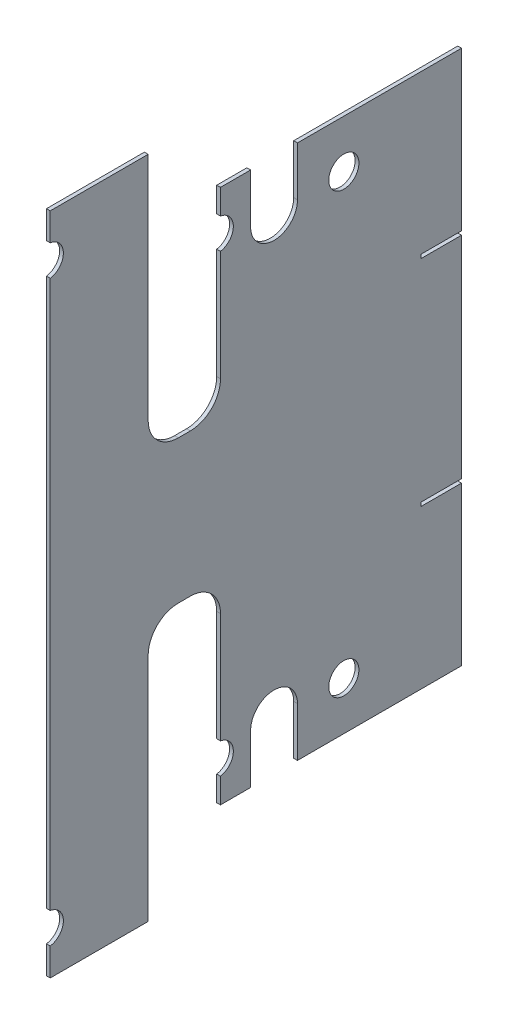
SolidWorks part; units mm, degrees
material "Custom Plastic"
ref_plane "X-Y Datum" through (0, 0, 0) normal (0, 0, 1) x (1, 0, 0)
ref_plane "X-Z Datum" through (0, 0, 0) normal (0, 1, 0) x (1, 0, 0)
ref_plane "Y-Z Datum" through (0, 0, 0) normal (1, 0, 0) x (0, 0, -1)
ref_plane "Plane1" through (-573.7606, 0, 0) normal (-1, 0, 0) x (0, 0, 1)
sketch "Sketch1" plane through (-573.7606, 0, 0) normal (-1, 0, 0) x (0, 0, 1)
  line L0 (55, 0) -> (-55, 0) construction
  line L1 (38.1, 225.425) -> (38.1, 183.8691)
  line L2 (-105.5624, -92.075) -> (-105.5624, -88.9)
  line L3 (-105.5624, 88.9) -> (-105.5624, 92.075)
  line L4 (-105.5624, 92.075) -> (-139.7, 92.075)
  line L5 (-105.5624, 88.9) -> (-139.7, 88.9)
  line L6 (-105.5624, -88.9) -> (-139.7, -88.9)
  line L7 (-139.7, -88.9) -> (-139.7, 88.9)
  line L8 (-139.7, 92.075) -> (-139.7, 225.425)
  line L9 (-139.7, 225.425) -> (-1.4023, 225.425)
  line L10 (-105.5624, -92.075) -> (-139.7, -92.075)
  line L11 (-139.7, -92.075) -> (-139.7, -225.425)
  line L12 (-139.7, -225.425) -> (-1.4023, -225.425)
  line L13 (63.5, -225.425) -> (63.5, -60.325)
  line L14 (63.5, 225.425) -> (63.5, 60.325)
  line L15 (63.5, -60.325) -> (124.46, -60.325)
  line L16 (63.5, 60.325) -> (124.46, 60.325)
  line L19 (207.01, 280.035) -> (124.46, 280.035)
  line L20 (124.46, 280.035) -> (124.46, 60.325)
  line L22 (207.01, -280.035) -> (124.46, -280.035)
  line L23 (124.46, -280.035) -> (124.46, -60.325)
  line L26 (207.01, -280.035) -> (207.01, 280.035)
  line L27 (-1.4023, 183.8691) -> (-1.4023, 225.425)
  line L28 (38.1, 225.425) -> (63.5, 225.425)
  line L29 (-1.4023, -183.8691) -> (-1.4023, -225.425)
  line L30 (38.1, -225.425) -> (38.1, -183.8691)
  line L31 (38.1, -225.425) -> (63.5, -225.425)
  arc A0 (38.1, 183.8691) -> (-1.4023, 183.8691) centre (18.3488, 183.8691) cw
  arc A1 (38.1, -183.8691) -> (-1.4023, -183.8691) centre (18.3488, -183.8691) ccw
  ellipse E1 centre (-40.4796, 184.9115) end of major axis (-41.5341, 197.7156) minor radius 12.7
  ellipse E2 centre (-40.4796, -184.9115) end of major axis (-41.5341, -197.7156) minor radius 12.7
  dimension "D1" = 184.15
  dimension "D2" = 177.8
  dimension "D3" = 34.1376
  dimension "D4" = 133.35
  dimension "D5" = 203.2
  dimension "D6" = 165.1
  dimension "D7" = 82.55
  dimension "D8" = 219.71
  dimension "D9" = 346.71
  dimension "D10" = 25.4
extrude "Boss-Extrude1" add sketch "Sketch1" along normal mid plane 3.175
ref_plane "Plane3" through (-457.2, 191.5789, 65.7345) normal (-1, 0, 0) x (0, 0, 1)
sketch "Sketch3" plane through (-457.2, 191.5789, 65.7345) normal (-1, 0, 0) x (0, 0, 1)
  circle A0 centre (0, 0) radius 13.081
  dimension "D1" = 26.162
extrude "Cut-Extrude1" cut sketch "Sketch3" along normal up to surface (118.1481 mm away) up to face at (-575.3481, -197.7156, -41.5341)
ref_plane "Plane4" through (-457.2, 243.7261, 209.0078) normal (1, 0, 0) x (0, 0, -1)
sketch "Sketch4" plane through (-457.2, 243.7261, 209.0078) normal (1, 0, 0) x (0, 0, -1)
  circle A0 centre (0, 0) radius 13.081
  dimension "D1" = 26.162
extrude "Cut-Extrude2" cut sketch "Sketch4" against normal up to surface (118.1481 mm away) up to face at (-575.3481, -197.7156, -41.5341)
mirror "Mirror1" about plane through (0, 0, 0) normal (0, 1, 0) of "Cut-Extrude2", "Cut-Extrude1"
fillet "Fillet1" radius 25.4 4 edges at (-573.7606, -60.325, 124.46) (-573.7606, -60.325, 63.5) (-573.7606, 60.325, 124.46) (-573.7606, 60.325, 63.5)
